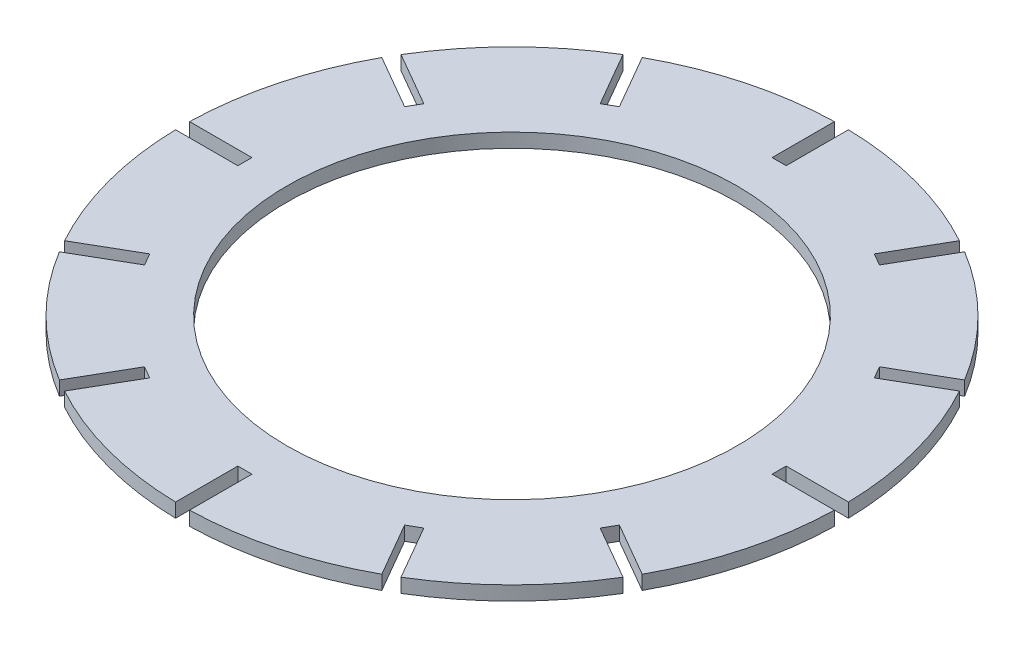
SolidWorks part; units mm, degrees
ref_plane "Front Plane" through (0, 0, 0) normal (0, 0, 1) x (1, 0, 0)
ref_plane "Top Plane" through (0, 0, 0) normal (0, 1, 0) x (1, 0, 0)
ref_plane "Right Plane" through (0, 0, 0) normal (1, 0, 0) x (0, 0, -1)
sketch "Sketch1" plane through (0, 0, 0) normal (0, 1, 0) x (1, 0, 0)
  circle A0 centre (0, 0) radius 48
  circle A1 centre (0, 0) radius 70.25
  dimension "D1" = 96
  dimension "D2" = 22.25
extrude "Boss-Extrude1" add sketch "Sketch1" along normal blind 3
sketch "Sketch2" plane through (0, 3, 0) normal (0, 1, 0) x (1, 0, 0)
  line L0 (0, 0) -> (-119.5598, 0) construction
  line L2 (-56.95, 1.5) -> (-70.25, 1.5)
  line L3 (-56.95, 1.5) -> (-56.95, -1.5)
  line L4 (-56.95, -1.5) -> (-70.25, -1.5)
  line L5 (-70.25, 1.5) -> (-70.25, -1.5)
  line L6 (-56.95, 1.5) -> (-70.25, -1.5) construction
  line L7 (-56.95, -1.5) -> (-70.25, 1.5) construction
  circle A0 centre (0, 0) radius 70.25 construction
  point P2 (-70.25, 0)
  point P5 (-63.6, 0)
  dimension "D1" = 3
  dimension "D2" = 13.3
extrude "Cut-Extrude1" cut sketch "Sketch2" against normal blind 3
pattern_circular "CirPattern1" count 12 over 360 about axis through (0, 0, 0) along (0, 1, 0) of "Cut-Extrude1"
